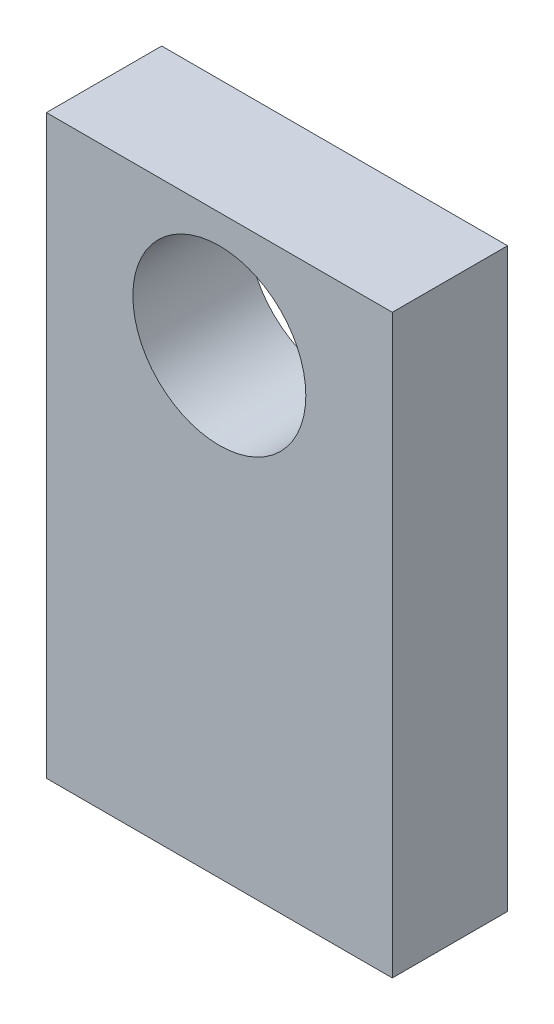
SolidWorks part; units mm, degrees
ref_plane "Front Plane" through (0, 0, 0) normal (0, 0, 1) x (1, 0, 0)
ref_plane "Top Plane" through (0, 0, 0) normal (0, 1, 0) x (1, 0, 0)
ref_plane "Right Plane" through (0, 0, 0) normal (1, 0, 0) x (0, 0, -1)
sketch "Sketch1" plane through (0, 0, 0) normal (0, 0, 1) x (1, 0, 0)
  line L1 (15, -25) -> (-15, -25)
  line L2 (15, -25) -> (15, 25)
  line L3 (15, 25) -> (-15, 25)
  line L4 (-15, -25) -> (-15, 25)
  line L5 (15, -25) -> (-15, 25) construction
  line L6 (15, 25) -> (-15, -25) construction
  circle A0 centre (0, 15) radius 7.5
  point P0 (0, 0)
  point P8 (0, 0)
  point P9 (0, 0)
  dimension "D1" = 15
  dimension "D2" = 50
  dimension "D3" = 10
  dimension "D4" = 30
extrude "Boss-Extrude1" add sketch "Sketch1" along normal blind 10
